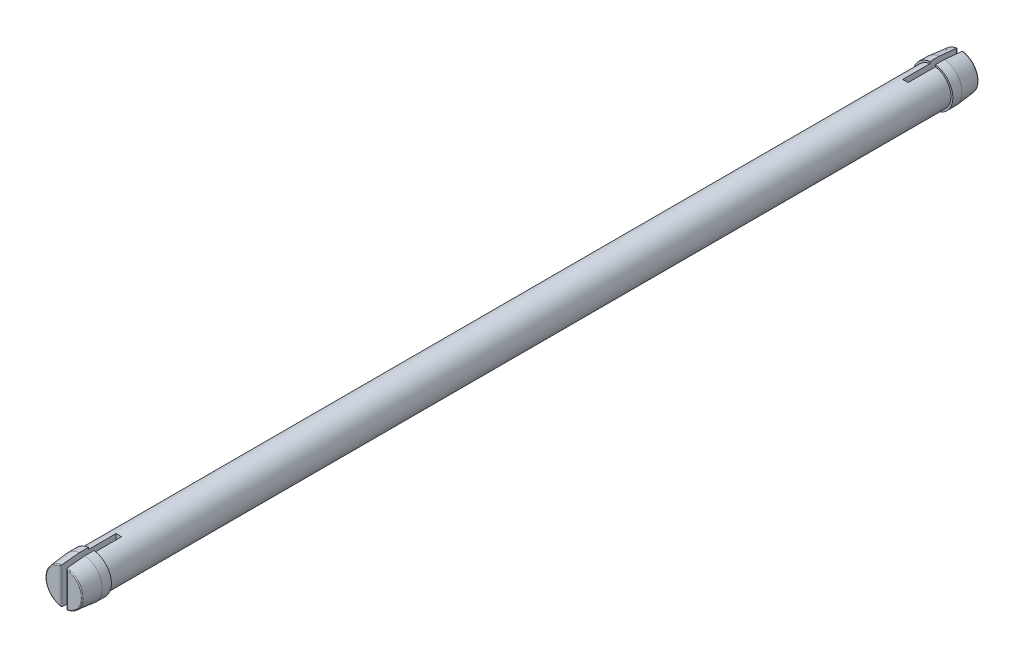
SolidWorks part; units mm, degrees
ref_plane "前视基准面" through (0, 0, 0) normal (0, 0, 1) x (1, 0, 0)
ref_plane "上视基准面" through (0, 0, 0) normal (0, 1, 0) x (1, 0, 0)
ref_plane "右视基准面" through (0, 0, 0) normal (1, 0, 0) x (0, 0, -1)
sketch "草图1" plane through (0, 0, 0) normal (0, 0, 1) x (1, 0, 0)
  circle A0 centre (0, 0) radius 2
extrude "凸台-拉伸1" add sketch "草图1" against normal blind 98
sketch "草图2" plane through (0, 0, 0) normal (0, 1, 0) x (1, 0, 0)
  line L0 (2, 98) -> (2, 95)
  line L1 (2, 0) -> (2, 98) construction
  line L2 (2, 95) -> (2.2, 95)
  line L3 (2.2, 95) -> (2.2, 96)
  line L4 (2.2, 96) -> (2, 98)
  line L5 (0, 98.4009) -> (0, 94.3) construction
revolve "旋转1" add sketch "草图2" angle 360 about L5
sketch "草图3" plane through (0, 0, 0) normal (0, 1, 0) x (1, 0, 0)
  line L0 (2, 0) -> (2, 3)
  line L1 (2, 0) -> (2, 95) construction
  line L2 (2, 3) -> (2.2, 3)
  line L3 (2.2, 3) -> (2.2, 2)
  line L4 (2.2, 2) -> (2, 0)
  line L5 (0, -0.7641) -> (0, 3.9858) construction
revolve "旋转2" add sketch "草图3" angle 360 about L5
sketch "草图4" plane through (0, 0, 0) normal (0, 0, 1) x (1, 0, 0)
  line L1 (-0.3, -2.3276) -> (0.3, -2.3276)
  line L2 (-0.3, -2.3276) -> (-0.3, 2.2642)
  line L3 (-0.3, 2.2642) -> (0.3, 2.2642)
  line L4 (0.3, -2.3276) -> (0.3, 2.2642)
extrude "切除-拉伸1" cut sketch "草图4" against normal blind 6
sketch "草图5" plane through (0, 0, -98) normal (0, 0, -1) x (-1, 0, 0)
  line L1 (-0.3, -2.3679) -> (0.3, -2.3679)
  line L2 (-0.3, -2.3679) -> (-0.3, 2.2584)
  line L3 (-0.3, 2.2584) -> (0.3, 2.2584)
  line L4 (0.3, -2.3679) -> (0.3, 2.2584)
extrude "切除-拉伸2" cut sketch "草图5" against normal blind 6
fillet "圆角1" radius 0.1 8 edges at (0.3, 0, -98) (2, 0, -98) (-0.3, 0, -98) (-2, 0, -98) (-2, 0, 0) (-0.3, 0, 0) (2, 0, 0) (0.3, 0, 0)
